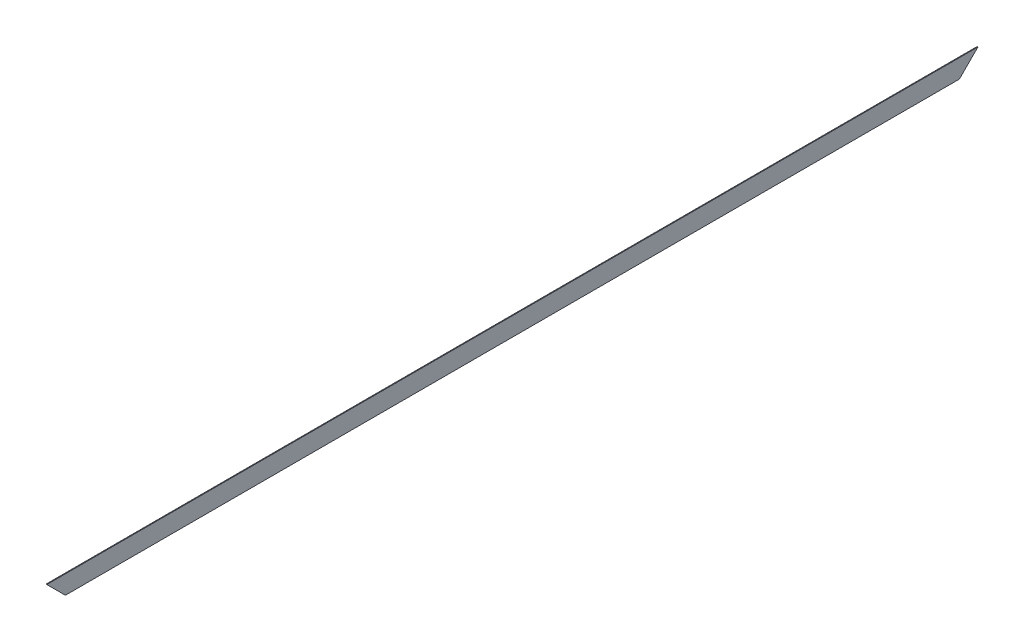
SolidWorks part; units mm, degrees
ref_plane "Alzado" through (0, 0, 0) normal (0, 0, 1) x (1, 0, 0)
ref_plane "Planta" through (0, 0, 0) normal (0, 1, 0) x (1, 0, 0)
ref_plane "Vista lateral" through (0, 0, 0) normal (1, 0, 0) x (0, 0, -1)
sketch "Croquis1" plane through (0, 0, 0) normal (0, 1, 0) x (1, 0, 0)
  line L1 (-46.4768, 18.3826) -> (1241.5232, 18.3826)
  line L2 (-46.4768, 18.3826) -> (-46.4768, -689.6174)
  line L3 (-46.4768, -689.6174) -> (1241.5232, -689.6174)
  line L4 (1241.5232, 18.3826) -> (1241.5232, -689.6174)
sketch "Croquis3" plane through (0, 0, 0) normal (0, 0, -1) x (-1, 0, 0)
  line L0 (-4.775, 0) -> (-4.775, 30)
  line L2 (-4.775, 0) -> (25.225, 0)
  line L3 (22.225, 3) -> (3.225, 3)
  line L4 (-1.775, 27) -> (-1.775, 8)
  arc A0 (-1.775, 27) -> (-4.775, 30) centre (-4.775, 27) ccw
  arc A1 (-1.775, 8) -> (3.225, 3) centre (3.225, 8) ccw
  arc A2 (22.225, 3) -> (25.225, 0) centre (22.225, 0) cw
extrude "Saliente-Extruir1" add sketch "Croquis3" against normal blind 1500
sketch "Croquis4" plane through (0, 0, 0) normal (1, 0, 0) x (0, 0, -1)
  line L0 (-1500, 0) -> (-1470, 0)
  line L1 (-1500, 0) -> (0, 0) construction
  line L2 (-1470, 0) -> (-1500, 30)
  line L3 (-1500, 30) -> (-1500, 0)
  line L4 (0, 0) -> (-30, 0)
  line L5 (18.3826, 0) -> (-689.6174, 0) construction
  line L6 (-30, 0) -> (0, 30)
  line L7 (0, 30) -> (0, 0)
extrude "Cortar-Extruir1" cut sketch "Croquis4" against normal blind 40 and the other way blind 10
